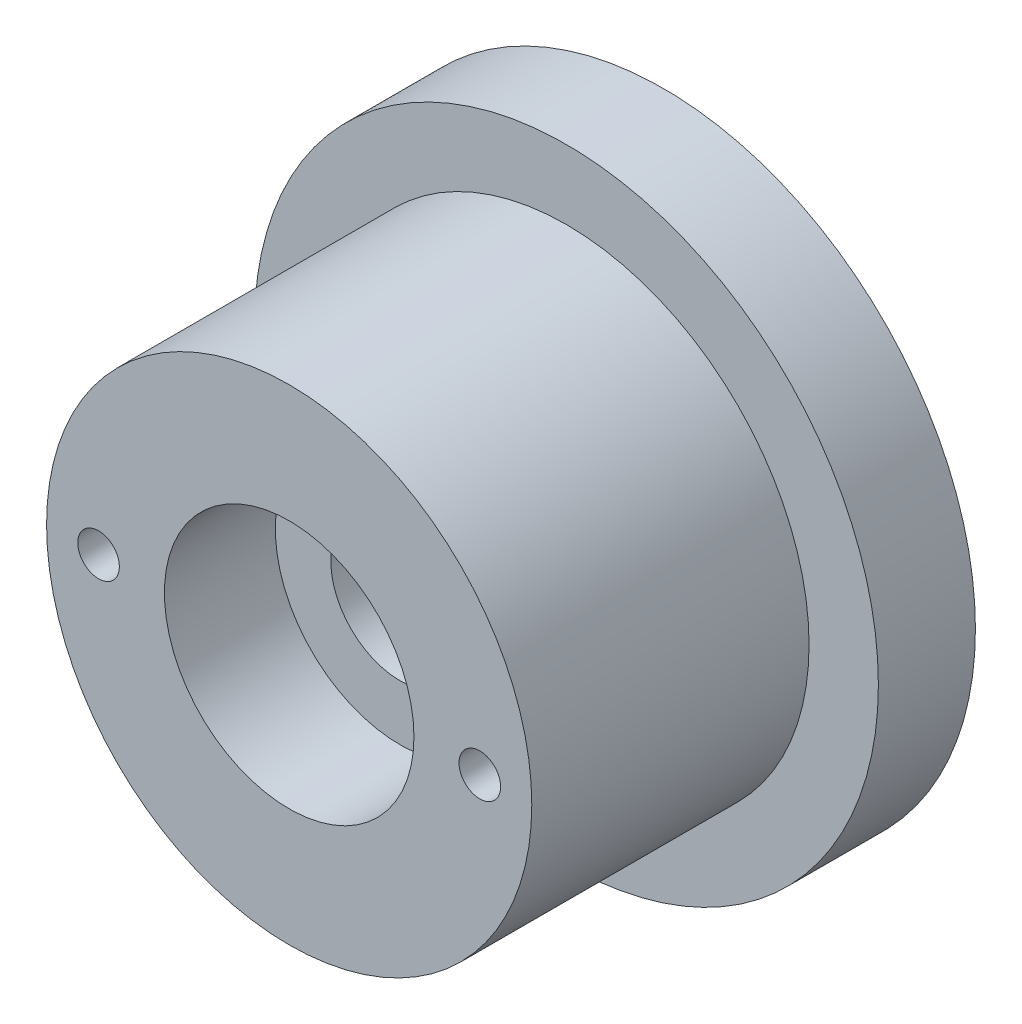
SolidWorks part; units mm, degrees
ref_plane "Front Plane" through (0, 0, 0) normal (0, 0, 1) x (1, 0, 0)
ref_plane "Top Plane" through (0, 0, 0) normal (0, 1, 0) x (1, 0, 0)
ref_plane "Right Plane" through (0, 0, 0) normal (1, 0, 0) x (0, 0, -1)
sketch "Sketch1" plane through (0, 0, 0) normal (0, 0, 1) x (1, 0, 0)
  circle A0 centre (0, 0) radius 17.5
  circle A1 centre (0, 0) radius 5
  circle A2 centre (-13.75, 0) radius 1.5
  circle A3 centre (13.75, 0) radius 1.5
  point P10 (0, 0)
  dimension "D1" = 35
  dimension "D2" = 10
  dimension "D3" = 3
  dimension "D4" = 13.75
  dimension "D5" = 2
extrude "Boss-Extrude1" add sketch "Sketch1" along normal mid plane 27
sketch "Sketch2" plane through (0, 0, -13.5) normal (0, 0, -1) x (-1, 0, 0)
  circle A0 centre (0, 0) radius 22.5
  circle A1 centre (0, 0) radius 17.5 construction
  circle A2 centre (0, 0) radius 17.5
  dimension "D1" = 45
extrude "Boss-Extrude2" add sketch "Sketch2" against normal blind 7
sketch "Sketch3" plane through (0, 0, 0) normal (0, 0, 1) x (1, 0, 0)
  circle A0 centre (0, 0) radius 7.5
  circle A1 centre (0, 0) radius 5 construction
  circle A2 centre (0, 0) radius 5
  dimension "D1" = 15
extrude "Boss-Extrude3" add sketch "Sketch3" along normal mid plane 17
sketch "Sketch4" plane through (0, 0, 13.5) normal (0, 0, 1) x (1, 0, 0)
  circle A0 centre (0, 0) radius 9
  dimension "D1" = 18
extrude "Cut-Extrude1" cut sketch "Sketch4" against normal blind 8
